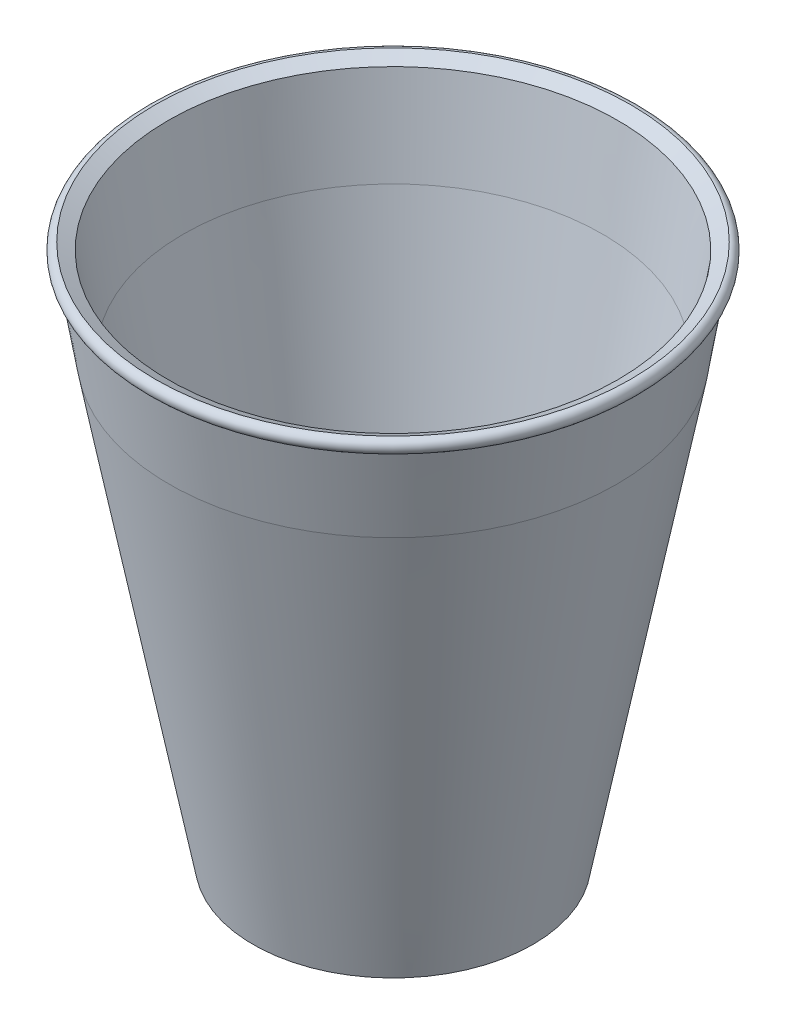
SolidWorks part; units mm, degrees
material "PP Copolymer"
ref_plane "Front Plane" through (0, 0, 0) normal (0, 0, 1) x (1, 0, 0)
ref_plane "Top Plane" through (0, 0, 0) normal (0, 1, 0) x (1, 0, 0)
ref_plane "Right Plane" through (0, 0, 0) normal (1, 0, 0) x (0, 0, -1)
sketch "Sketch1" plane through (0, 0, 0) normal (0, 0, 1) x (1, 0, 0)
  line L0 (0, 0) -> (0, -77) construction
  line L1 (-20, -77) -> (20, -77) construction
  line L2 (-34, 0) -> (34, 0) construction
  line L3 (-32.1307, -1) -> (-34, 0)
  line L6 (21.5561, -64) -> (20, -77) construction
  line L7 (-12.6, -77) -> (-12.3226, -76.7781)
  line L9 (-34, -2) -> (34, -2) construction
  line L10 (-35, -1) -> (35, -1) construction
  line L11 (-32, -14) -> (32, -14) construction
  line L12 (-34, -2) -> (-32, -14)
  line L15 (34, -2) -> (32, -14) construction
  line L16 (32, -14) -> (27.5, -50.547) construction
  line L17 (27.5, -50.547) -> (23.9354, -64) construction
  line L19 (21.5561, -64) -> (23.9354, -64) construction
  line L22 (0, -73.7) -> (-18.5926, -73.7)
  line L27 (-29.964, -14) -> (-32.1307, -1)
  line L28 (-29.964, -14) -> (-18.5926, -73.7)
  line L29 (-20, -77) -> (-12.6, -77)
  line L30 (-12.6, -76.6) -> (-12.6, -75.2)
  line L31 (-12.6, -75.2) -> (0, -75.2)
  line L32 (0, -75.2) -> (0, -73.7)
  line L33 (-32, -14) -> (-20, -77)
  line L34 (-12.3851, -76.6) -> (-12.6, -76.6)
  arc A0 (-34, -2) -> (-34, 0) centre (-34, -1) cw
  arc A1 (34, -2) -> (34, 0) centre (34, -1) ccw construction
  arc A2 (-12.3226, -76.7781) -> (-12.3851, -76.6) centre (-12.3851, -76.7) ccw
  point P6 (0, -77)
  point P11 (0, 0)
  point P22 (0, -2)
  point P25 (0, -1)
  point P28 (0, -14)
  point P32 (-12.1, -76.6)
  dimension "D7" = 0.1
  dimension "D1" = 77
  dimension "D2" = 40
  dimension "D3" = 68
  dimension "D4" = 0.4
  dimension "D5" = 2
  dimension "D6" = 0.5
  dimension "D9" = 2
  dimension "D10" = 68
  dimension "D11" = 70
  dimension "D12" = 1
  dimension "D13" = 14
  dimension "D14" = 64
  dimension "D15" = 1.8
  dimension "D20" = 12.6
  dimension "D21" = 3.3
revolve "Revolve1" add sketch "Sketch1" angle 360 about L0
